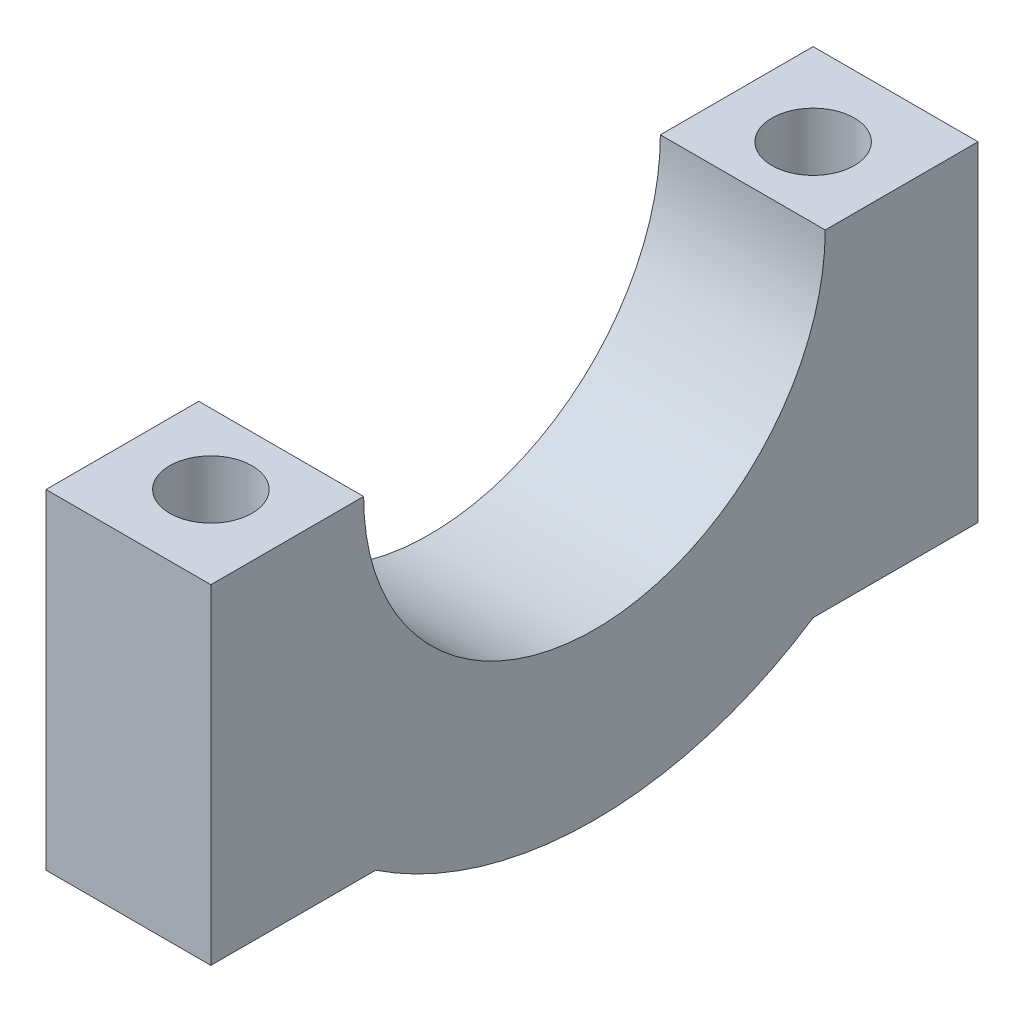
SolidWorks part; units mm, degrees
ref_plane "Front Plane" through (0, 0, 0) normal (0, 0, 1) x (1, 0, 0)
ref_plane "Top Plane" through (0, 0, 0) normal (0, 1, 0) x (1, 0, 0)
ref_plane "Right Plane" through (0, 0, 0) normal (1, 0, 0) x (0, 0, -1)
sketch "Sketch1" plane through (0, 0, 0) normal (1, 0, 0) x (0, 0, -1)
  line L1 (-17.78, 0) -> (17.78, 0) construction
  line L2 (-17.78, 0) -> (-29.5485, 0)
  line L3 (-29.5485, 0) -> (-29.5485, -25.4)
  line L4 (-29.5485, -25.4) -> (-16.8485, -25.4)
  line L5 (17.78, 0) -> (29.5485, 0)
  line L6 (29.5485, 0) -> (29.5485, -25.4)
  line L7 (29.5485, -25.4) -> (16.8485, -25.4)
  arc A0 (-17.78, 0) -> (17.78, 0) centre (0, 0) ccw
  arc A1 (-16.8485, -25.4) -> (16.8485, -25.4) centre (0, 0) ccw
  dimension "D1" = 17.78
  dimension "D2" = 12.7
  dimension "D6" = 30.48
  dimension "D3" = 12.7
  dimension "D4" = 25.4
  dimension "D5" = 25.4
extrude "Boss-Extrude1" add sketch "Sketch1" along normal blind 12.7
sketch "Sketch2" plane through (0, -25.4, 0) normal (0, -1, 0) x (1, 0, 0)
  line L0 (-2.5848, 0) -> (-12.0772, 0) construction
  line L1 (0, 23.1985) -> (6.35, 23.1985) construction
  line L2 (0, 29.5485) -> (0, 16.8485) construction
  line L3 (6.35, 23.1985) -> (6.35, 29.5485) construction
  line L4 (12.7, 29.5485) -> (0, 29.5485) construction
  circle A0 centre (6.35, 23.1985) radius 3.175
  circle A1 centre (6.35, -23.1985) radius 3.175
  dimension "D1" = 6.35
extrude "Cut-Extrude1" cut sketch "Sketch2" against normal through all
